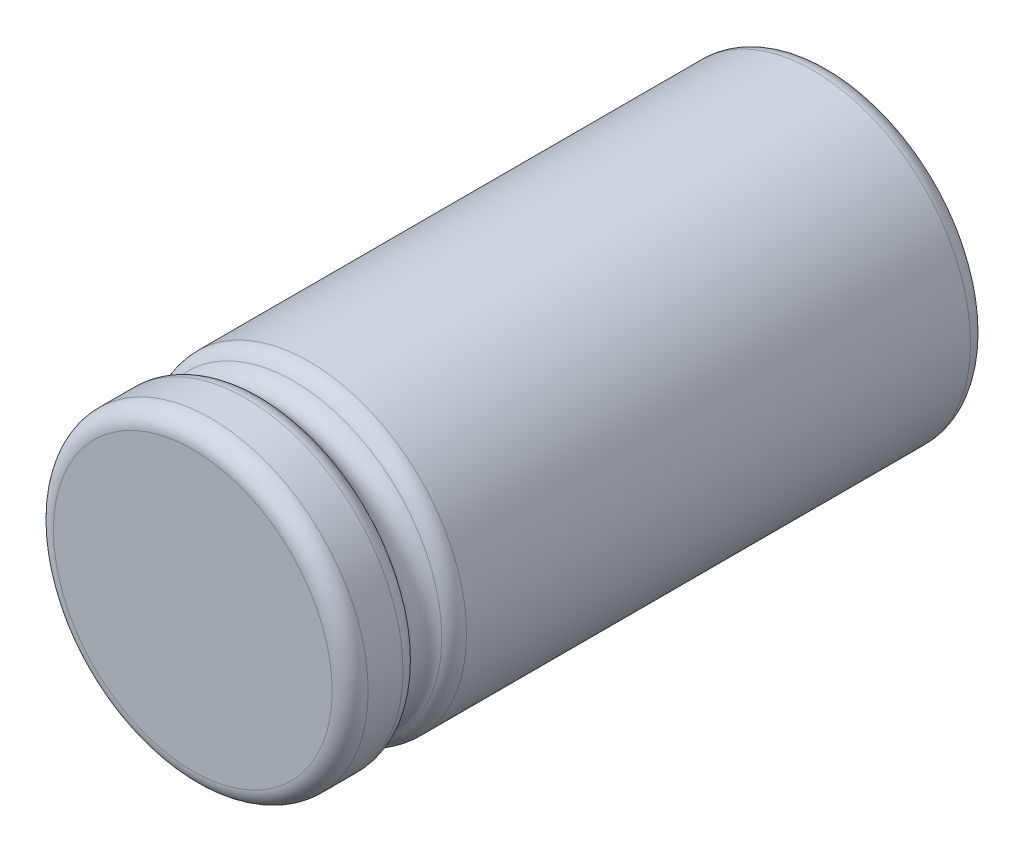
SolidWorks part; units mm, degrees
ref_plane "Front Plane" through (0, 0, 0) normal (0, 0, 1) x (1, 0, 0)
ref_plane "Top Plane" through (0, 0, 0) normal (0, 1, 0) x (1, 0, 0)
ref_plane "Right Plane" through (0, 0, 0) normal (1, 0, 0) x (0, 0, -1)
sketch "Sketch1" plane through (0, 0, 0) normal (0, 0, 1) x (1, 0, 0)
  circle A0 centre (0, 0) radius 17.5
  dimension "D1" = 35
extrude "Boss-Extrude1" add sketch "Sketch1" along normal blind 71
fillet "Fillet1" radius 2 2 edges at (17.5, 0, 71) (17.5, 0, 0)
sketch "Sketch2" plane through (0, 0, 0) normal (0, 1, 0) x (1, 0, 0)
  line L0 (17.5, -69) -> (17.5, -2) construction
  circle A0 centre (17.5, -61.5903) radius 2.0611
  point P4 (17.5, -61.5903)
sweep "Cut-Sweep1" cut profiles "Sketch2" path edge at (17.5, 0, 69)
fillet "Fillet2" radius 2 2 edges at (-17.5, 0, 63.6514) (17.5, 0, 59.5292)
